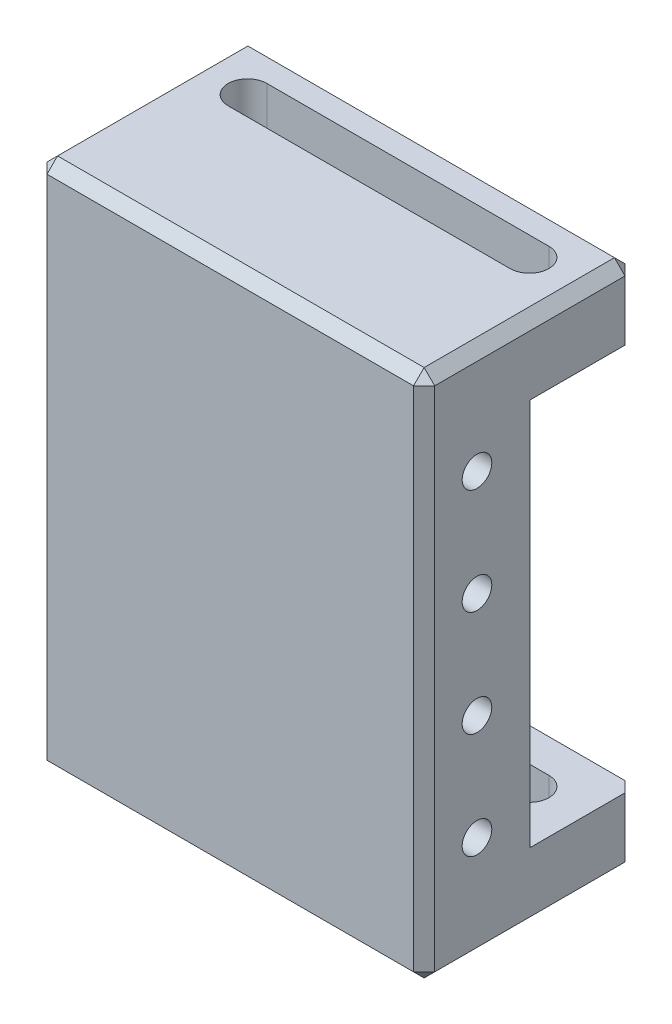
SolidWorks part; units mm, degrees
material "1060 Alloy"
ref_plane "Front Plane" through (0, 0, 0) normal (0, 0, 1) x (1, 0, 0)
ref_plane "Top Plane" through (0, 0, 0) normal (0, 1, 0) x (1, 0, 0)
ref_plane "Right Plane" through (0, 0, 0) normal (1, 0, 0) x (0, 0, -1)
sketch "Sketch1" plane through (0, 0, 0) normal (0, 0, 1) x (1, 0, 0)
  line L1 (-27.5, 32.5) -> (27.5, 32.5)
  line L2 (-27.5, 32.5) -> (-27.5, -32.5)
  line L3 (-27.5, -32.5) -> (27.5, -32.5)
  line L4 (27.5, 32.5) -> (27.5, -32.5)
  line L5 (-27.5, 32.5) -> (27.5, -32.5) construction
  line L6 (-27.5, -32.5) -> (27.5, 32.5) construction
  point P0 (0, 0)
  dimension "D1" = 65
  dimension "D2" = 55
extrude "Boss-Extrude1" add sketch "Sketch1" along normal blind 10
sketch "Sketch2" plane through (0, 0, 0) normal (0, 0, -1) x (-1, 0, 0)
  line L0 (27.5, 32.5) -> (27.5, -32.5) construction
  line L1 (-27.5, 32.5) -> (27.5, 32.5)
  line L2 (-27.5, 32.5) -> (-27.5, 27.5)
  line L3 (-27.5, 27.5) -> (27.5, 27.5)
  line L4 (27.5, 32.5) -> (27.5, 27.5)
  line L6 (-27.5, -32.5) -> (27.5, -32.5)
  line L7 (-27.5, -32.5) -> (-27.5, -27.5)
  line L8 (-27.5, -27.5) -> (27.5, -27.5)
  line L9 (27.5, -32.5) -> (27.5, -27.5)
  dimension "D1" = 5
  dimension "D2" = 5
extrude "Boss-Extrude2" add sketch "Sketch2" along normal blind 15
sketch "Sketch3" plane through (0, -32.5, 0) normal (0, -1, 0) x (1, 0, 0)
  line L0 (-20.05, -7.5) -> (19.95, -7.5) construction
  line L1 (-20.05, -4.75) -> (19.95, -4.75)
  line L2 (-20.05, -10.25) -> (19.95, -10.25)
  line L3 (27.5, 10) -> (27.5, -15) construction
  line L4 (27.5, -15) -> (-27.5, -15) construction
  arc A0 (-20.05, -4.75) -> (-20.05, -10.25) centre (-20.05, -7.5) ccw
  arc A1 (19.95, -10.25) -> (19.95, -4.75) centre (19.95, -7.5) ccw
  point P2 (-0.05, -7.5)
  dimension "D1" = 7.55
  dimension "D2" = 7.5
extrude "Cut-Extrude1" cut sketch "Sketch3" against normal blind 104
sketch "Sketch4" plane through (0, 0, 10) normal (0, 0, 1) x (1, 0, 0)
  line L1 (-27.5, 32.5) -> (27.5, 32.5)
  line L2 (-27.5, 32.5) -> (-27.5, -32.5)
  line L3 (-27.5, -32.5) -> (27.5, -32.5)
  line L4 (27.5, 32.5) -> (27.5, -32.5)
extrude "Boss-Extrude3" add sketch "Sketch4" along normal blind 5
hole_wizard "M5 Tapped Hole2" positions "Sketch11" profile "Sketch12" tap size "M5" standard "DIN"
sketch "Sketch11" plane through (27.5, 0, 0) normal (1, 0, 0) x (0, 0, -1)
  line L0 (-15, 32.5) -> (15, 32.5) construction
  line L1 (-15, -32.5) -> (15, -32.5) construction
  line L2 (-15, -32.5) -> (-15, 32.5) construction
  point P0 (-7.5, 22.5)
  point P2 (-7.5, 7.5)
  point P4 (-7.4999, -7.5)
  point P6 (-7.4999, -22.5)
  dimension "D1" = 10
  dimension "D2" = 10
  dimension "D3" = 15
  dimension "D4" = 15
  dimension "D5" = 15
  dimension "D6" = 7.5
  dimension "D7" = 7.5001
sketch "Sketch12" plane through (27.5, 22.5, 7.5) normal (0, 1, 0) x (0, 0, -1)
  line L0 (0, 0) -> (0, 15.2618)
  line L1 (0, 15.2618) -> (2.1, 14)
  line L2 (2.1, 14) -> (2.1, 0)
  line L5 (2.1, 0) -> (0, 0)
  line L10 (0, 15.2618) -> (-2.1, 14) construction
  line L11 (0, -6.35) -> (0, 107.95) construction
  dimension "Tap Drill Dia." = 4.2
  dimension "Tap Drill Depth" = 14
  dimension "Drill Angle" = 118
cosmetic thread "Hole Thread5" parameters "D1"=10, "D2"=5
cosmetic thread "Hole Thread6" parameters "D1"=10, "D2"=5
cosmetic thread "Hole Thread7" parameters "D1"=10, "D2"=5
cosmetic thread "Hole Thread8" parameters "D1"=10, "D2"=5
ref_plane "Plane2" through (0, 0, 0) normal (1, 0, 0) x (0, 0, -1)
mirror "Mirror2" about plane through (0, 0, 0) normal (1, 0, 0) of "M5 Tapped Hole2"
sketch "Sketch13" plane through (0, -32.5, 0) normal (0, -1, 0) x (1, 0, 0)
  line L0 (-20.05, -7.5) -> (19.95, -7.5) construction
  line L1 (-20.05, -4.75) -> (19.95, -4.75)
  line L2 (-20.05, -10.25) -> (19.95, -10.25)
  line L4 (-27.5, 15) -> (27.5, 15)
  line L5 (-27.5, 15) -> (-27.5, -15)
  line L6 (-27.5, -15) -> (27.5, -15)
  line L7 (27.5, 15) -> (27.5, -15)
  arc A0 (-20.05, -4.75) -> (-20.05, -10.25) centre (-20.05, -7.5) ccw
  arc A1 (19.95, -10.25) -> (19.95, -4.75) centre (19.95, -7.5) ccw
  point P4 (-0.05, -7.5)
extrude "Boss-Extrude4" add sketch "Sketch13" along normal blind 5
ref_plane "Plane3" through (0, 0, 0) normal (0, -1, 0) x (-1, 0, 0)
mirror "Mirror3" about plane through (0, 0, 0) normal (0, -1, 0) of "Boss-Extrude4"
chamfer "Chamfer2" distance 1.5 angle 45 14 edges at (-27.5, 32.5, -15) (0, 37.5, -15) (27.5, 32.5, -15) (27.5, -32.5, -15) (0, -37.5, -15) (-27.5, -32.5, -15) (-27.5, 37.5, 0) (0, 37.5, 15) (27.5, 37.5, 0) (-27.5, 0, 15) (27.5, 0, 15) (27.5, -37.5, 0) (0, -37.5, 15) (-27.5, -37.5, 0)
